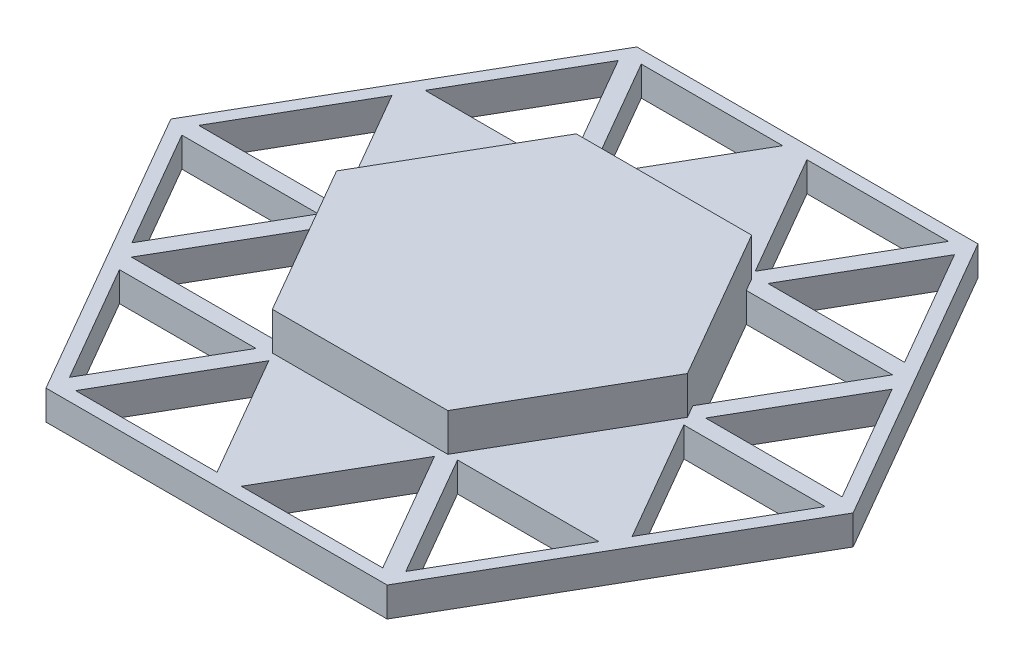
SolidWorks part; units mm, degrees
ref_plane "前视基准面" through (0, 0, 0) normal (0, 0, 1) x (1, 0, 0)
ref_plane "上视基准面" through (0, 0, 0) normal (0, 1, 0) x (1, 0, 0)
ref_plane "右视基准面" through (0, 0, 0) normal (1, 0, 0) x (0, 0, -1)
other "Configuration Table"
sketch "草图1" plane through (0, 0, 0) normal (0, 1, 0) x (1, 0, 0)
  line L22 (-112.5591, 19.6655) -> (-92.3114, -15.4045)
  line L23 (-92.3114, -15.4045) -> (-72.0637, -50.4746)
  line L24 (-72.0637, -50.4746) -> (-31.5683, -50.4746)
  line L25 (-31.5683, -50.4746) -> (8.9271, -50.4746)
  line L26 (8.9271, -50.4746) -> (29.1748, -15.4045)
  line L27 (29.1748, -15.4045) -> (49.4225, 19.6655)
  line L28 (49.4225, 19.6655) -> (29.1748, 54.7355)
  line L29 (29.1748, 54.7355) -> (8.9271, 89.8056)
  line L30 (8.9271, 89.8056) -> (-31.5683, 89.8056)
  line L31 (-31.5683, 89.8056) -> (-72.0637, 89.8056)
  line L32 (-72.0637, 89.8056) -> (-92.3114, 54.7355)
  line L33 (-92.3114, 54.7355) -> (-112.5591, 19.6655)
  line L44 (-68.0222, 86.8056) -> (-34.4551, 86.8056)
  line L53 (-51.2386, 57.7355) -> (-34.4551, 86.8056)
  line L55 (-68.0222, 86.8056) -> (-51.2386, 57.7355)
  line L74 (8.3498, 84.8056) -> (24.556, 56.7355)
  line L75 (24.556, 56.7355) -> (-7.8565, 56.7355)
  line L76 (-7.8565, 56.7355) -> (8.3498, 84.8056)
  line L77 (-9.0112, 52.7355) -> (8.3498, 22.6655)
  line L78 (8.3498, 22.6655) -> (25.7107, 52.7355)
  line L79 (25.7107, 52.7355) -> (-9.0112, 52.7355)
  line L80 (28.5975, 49.7355) -> (44.8037, 21.6655)
  line L81 (44.8037, 21.6655) -> (12.3912, 21.6655)
  line L82 (12.3912, 21.6655) -> (28.5975, 49.7355)
  line L83 (11.2365, 17.6655) -> (28.0201, -11.4045)
  line L84 (28.0201, -11.4045) -> (44.8037, 17.6655)
  line L85 (44.8037, 17.6655) -> (11.2365, 17.6655)
  line L86 (-8.4338, -16.4045) -> (25.1333, -16.4045)
  line L87 (25.1333, -16.4045) -> (8.3498, -45.4746)
  line L88 (8.3498, -45.4746) -> (-8.4338, -16.4045)
  line L89 (-11.8979, -18.4045) -> (4.8856, -47.4746)
  line L90 (-28.6815, -47.4746) -> (4.8856, -47.4746)
  line L91 (-11.8979, -18.4045) -> (-28.6815, -47.4746)
  line L92 (-28.6815, 86.8056) -> (4.8856, 86.8056)
  line L93 (4.8856, 86.8056) -> (-11.8979, 57.7355)
  line L94 (-28.6815, 86.8056) -> (-11.8979, 57.7355)
  line L95 (-88.2699, 55.7355) -> (-71.4864, 84.8056)
  line L96 (-71.4864, 84.8056) -> (-54.7028, 55.7355)
  line L97 (-54.7028, 55.7355) -> (-88.2699, 55.7355)
  line L98 (-107.9403, 21.6655) -> (-91.1567, 50.7355)
  line L99 (-91.1567, 50.7355) -> (-74.3731, 21.6655)
  line L100 (-74.3731, 21.6655) -> (-107.9403, 21.6655)
  line L101 (-75.5278, 17.6655) -> (-107.9403, 17.6655)
  line L102 (-107.9403, 17.6655) -> (-91.7341, -10.4045)
  line L103 (-91.7341, -10.4045) -> (-75.5278, 17.6655)
  line L104 (-88.8473, -13.4045) -> (-54.1254, -13.4045)
  line L105 (-54.1254, -13.4045) -> (-71.4864, 16.6655)
  line L106 (-71.4864, 16.6655) -> (-88.8473, -13.4045)
  line L110 (-68.0222, -47.4746) -> (-34.4551, -47.4746)
  line L111 (-51.2386, -18.4045) -> (-34.4551, -47.4746)
  line L112 (-51.2386, -18.4045) -> (-68.0222, -47.4746)
  line L113 (-87.6926, -17.4045) -> (-71.4864, -45.4746)
  line L115 (-55.2801, -17.4045) -> (-71.4864, -45.4746)
  line L116 (-55.2801, -17.4045) -> (-87.6926, -17.4045)
  point P0 (0, 0)
  point P15 (-69.7543, -48.4746)
  point P79 (0, 0)
  point P100 (0, 0)
extrude "凸台-拉伸1" add sketch "草图1" along normal blind 7
sketch "草图2" plane through (0, 7, 0) normal (0, 1, 0) x (1, 0, 0)
  line L5 (-71.4864, 16.6655) -> (-73.2184, 19.6655)
  line L6 (-73.2184, 19.6655) -> (-52.3934, 55.7355)
  line L7 (-10.7432, 55.7355) -> (10.0818, 19.6655)
  line L8 (-52.3934, 55.7355) -> (-10.7432, 55.7355)
  line L9 (-52.3934, -16.4045) -> (-10.7432, -16.4045)
  line L10 (-71.4864, 16.6655) -> (-52.3934, -16.4045)
  line L11 (-10.7432, -16.4045) -> (10.0818, 19.6655)
extrude "凸台-拉伸2" add sketch "草图2" along normal blind 9
